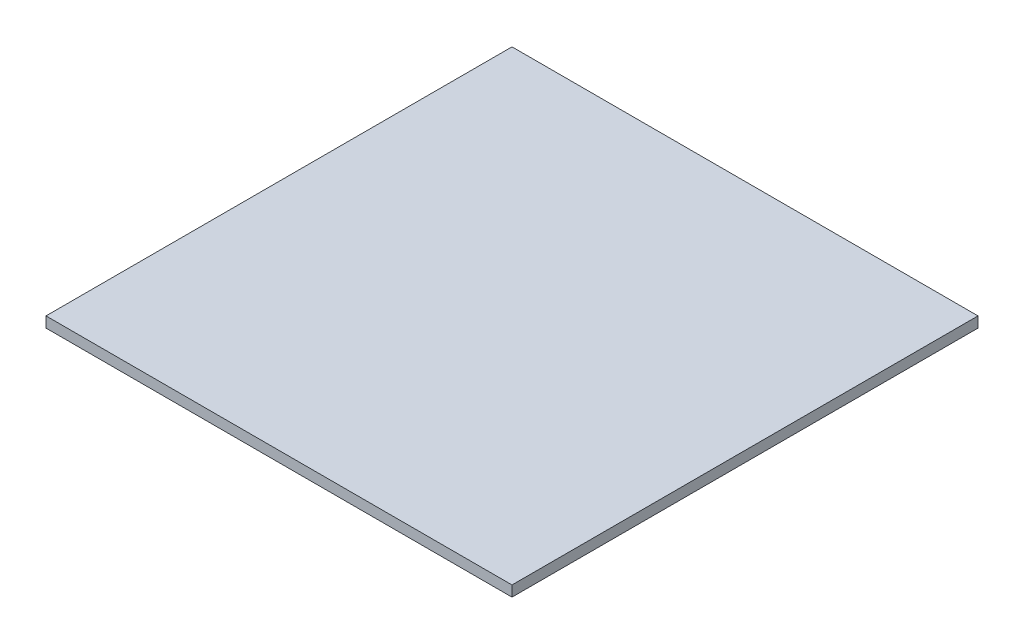
SolidWorks part; units mm, degrees
ref_plane "Front Plane" through (0, 0, 0) normal (0, 0, 1) x (1, 0, 0)
ref_plane "Top Plane" through (0, 0, 0) normal (0, 1, 0) x (1, 0, 0)
ref_plane "Right Plane" through (0, 0, 0) normal (1, 0, 0) x (0, 0, -1)
sketch "Sketch1" plane through (0, 0, 0) normal (0, 1, 0) x (1, 0, 0)
  line L1 (-110, -110) -> (110, -110)
  line L2 (-110, -110) -> (-110, 110)
  line L3 (-110, 110) -> (110, 110)
  line L4 (110, -110) -> (110, 110)
  line L5 (-110, -110) -> (110, 110) construction
  line L6 (-110, 110) -> (110, -110) construction
  point P0 (0, 0)
  dimension "D1" = 220
  dimension "D2" = 220
extrude "Boss-Extrude1" add sketch "Sketch1" along normal blind 5
